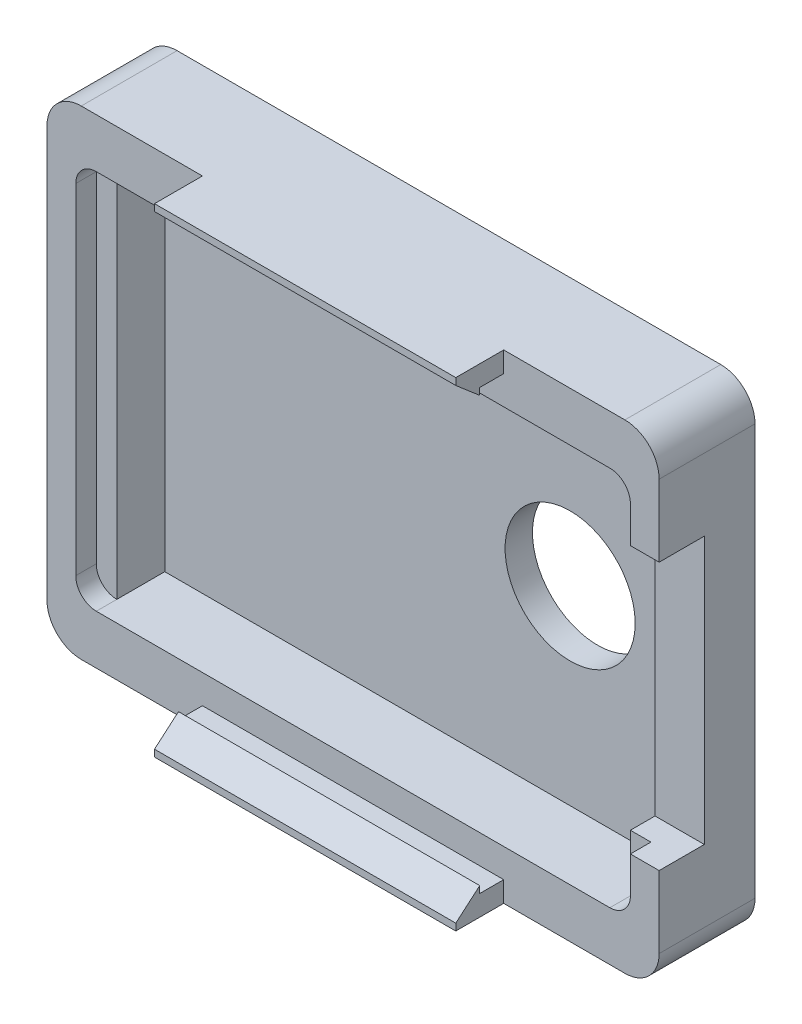
SolidWorks part; units mm, degrees
ref_plane "Alzado" through (0, 0, 0) normal (0, 0, 1) x (1, 0, 0)
ref_plane "Planta" through (0, 0, 0) normal (0, 1, 0) x (1, 0, 0)
ref_plane "Vista lateral" through (0, 0, 0) normal (1, 0, 0) x (0, 0, -1)
sketch "Croquis1" plane through (0, 0, 0) normal (0, 0, 1) x (1, 0, 0)
  line L1 (-22.35, -17.5) -> (22.35, -17.5)
  line L2 (-22.35, -17.5) -> (-22.35, 17.5)
  line L3 (-22.35, 17.5) -> (22.35, 17.5)
  line L4 (22.35, -17.5) -> (22.35, 17.5)
  line L5 (-22.35, -17.5) -> (22.35, 17.5) construction
  line L6 (-22.35, 17.5) -> (22.35, -17.5) construction
  line L11 (-11.35, 14) -> (-6.35, 14)
  line L12 (-11.35, 14) -> (-11.35, 9)
  line L13 (-11.35, 9) -> (-6.35, 9)
  line L14 (-6.35, 14) -> (-6.35, 9)
  circle A0 centre (10.85, 0) radius 4.75
  point P0 (0, 0)
  dimension "D3" = 9.5
  dimension "D1" = 35
  dimension "D2" = 44.7
  dimension "D4" = 11.5
  dimension "D5" = 11
  dimension "D6" = 5
  dimension "D7" = 5
  dimension "D8" = 3.5
extrude "Saliente-Extruir1" add sketch "Croquis1" along normal blind 2 contours L11 L14 L1 L4 L3 L2 L12 A0
sketch "Croquis2" plane through (0, 0, 2) normal (0, 0, 1) x (1, 0, 0)
  line L0 (-22.35, -17.5) -> (22.35, -17.5) construction
  line L1 (22.35, 17.5) -> (-22.35, 17.5) construction
  line L2 (22.35, -17.5) -> (22.35, 17.5) construction
  line L3 (-22.35, 17.5) -> (-22.35, -17.5) construction
  line L4 (-22.35, -17.5) -> (22.35, -17.5)
  line L5 (22.35, 17.5) -> (-22.35, 17.5)
  line L6 (22.35, -17.5) -> (22.35, 17.5)
  line L7 (-22.35, 17.5) -> (-22.35, -17.5)
  line L9 (-20.25, -13.9) -> (20.25, -13.9)
  line L10 (-20.25, -13.9) -> (-20.25, 13.9)
  line L11 (-20.25, 13.9) -> (20.25, 13.9)
  line L12 (20.25, -13.9) -> (20.25, 13.9)
  line L13 (-20.25, -13.9) -> (20.25, 13.9) construction
  line L14 (-20.25, 13.9) -> (20.25, -13.9) construction
  point P4 (0, 0)
  dimension "D1" = 40.5
  dimension "D2" = 27.8
extrude "Saliente-Extruir2" add sketch "Croquis2" along normal blind 5
fillet "Redondeo1" radius 1.5 4 edges at (20.25, -13.9, 4.5) (20.25, 13.9, 4.5) (-20.25, -13.9, 4.5) (-20.25, 13.9, 4.5)
fillet "Redondeo2" radius 2.5 4 edges at (22.35, -17.5, 3.5) (22.35, 17.5, 3.5) (-22.35, -17.5, 3.5) (-22.35, 17.5, 3.5)
sketch "Croquis3" [suppressed] plane through (0, -17.5, 0) normal (0, -1, 0) x (1, 0, 0)
  line L1 (-10.6695, 15.4652) -> (9.8413, 15.4652)
  line L2 (-10.6695, 15.4652) -> (-10.6695, 7.9232)
  line L3 (-10.6695, 7.9232) -> (9.8413, 7.9232)
  line L4 (9.8413, 15.4652) -> (9.8413, 7.9232)
  line L5 (-10.6695, 15.4652) -> (9.8413, 7.9232) construction
  line L6 (-10.6695, 7.9232) -> (9.8413, 15.4652) construction
  point P0 (-0.4141, 11.6942)
sketch "Croquis4" plane through (0, 0, 2) normal (0, 0, 1) x (1, 0, 0)
  line L0 (-20.25, 12.4) -> (-20.25, -12.4) construction
  line L1 (20.25, -12.4) -> (20.25, 12.4) construction
  line L2 (-20.25, 12.4) -> (-20.25, -12.4)
  line L3 (20.25, -12.4) -> (20.25, 12.4)
  line L4 (18.75, -13.9) -> (18.75, 13.9)
  line L5 (-18.75, -13.9) -> (-18.75, 13.9)
  arc A0 (-18.75, 13.9) -> (-20.25, 12.4) centre (-18.75, 12.4) ccw construction
  arc A1 (-20.25, -12.4) -> (-18.75, -13.9) centre (-18.75, -12.4) ccw construction
  arc A2 (20.25, 12.4) -> (18.75, 13.9) centre (18.75, 12.4) ccw construction
  arc A3 (18.75, -13.9) -> (20.25, -12.4) centre (18.75, -12.4) ccw construction
  arc A4 (-18.75, 13.9) -> (-20.25, 12.4) centre (-18.75, 12.4) ccw
  arc A5 (-20.25, -12.4) -> (-18.75, -13.9) centre (-18.75, -12.4) ccw
  arc A6 (20.25, 12.4) -> (18.75, 13.9) centre (18.75, 12.4) ccw
  arc A7 (18.75, -13.9) -> (20.25, -12.4) centre (18.75, -12.4) ccw
extrude "Saliente-Extruir3" add sketch "Croquis4" along normal blind 3.5
sketch "Croquis5" plane through (22.35, 0, 0) normal (1, 0, 0) x (0, 0, -1)
  line L0 (-7, -15) -> (-7, 15) construction
  line L1 (-7, -9.75) -> (-3.7, -9.75)
  line L2 (-7, -9.75) -> (-7, 9.75)
  line L3 (-7, 9.75) -> (-3.7, 9.75)
  line L4 (-3.7, -9.75) -> (-3.7, 9.75)
  point P6 (-3.7, 0)
  dimension "D1" = 19.5
  dimension "D2" = 3.3
extrude "Cortar-Extruir1" cut sketch "Croquis5" against normal blind 5.5
sketch "Croquis6" plane through (0, 0, 7) normal (0, 0, 1) x (1, 0, 0)
  line L0 (-19.85, -17.5) -> (19.85, -17.5) construction
  line L1 (11, -17.5) -> (-11, -17.5)
  line L2 (11, -17.5) -> (11, -15.5)
  line L3 (11, -15.5) -> (-11, -15.5)
  line L4 (-11, -17.5) -> (-11, -15.5)
  line L5 (19.85, 17.5) -> (-19.85, 17.5) construction
  line L6 (11, 17.5) -> (-11, 17.5)
  line L7 (11, 17.5) -> (11, 15.5)
  line L8 (11, 15.5) -> (-11, 15.5)
  line L9 (-11, 17.5) -> (-11, 15.5)
  point P12 (0, -15.5)
  point P14 (0, 17.5)
  point P16 (0, 15.5)
  dimension "D1" = 22
  dimension "D2" = 22
  dimension "D3" = 2
  dimension "D4" = 2
extrude "Saliente-Extruir4" add sketch "Croquis6" along normal blind 3.5
sketch "Croquis7" plane through (11, 0, 0) normal (1, 0, 0) x (0, 0, -1)
  line L0 (-10.5, -17) -> (-8.75, -15.5)
  line L1 (-10.5, -17.5) -> (-10.5, -15.5) construction
  line L2 (-8.75, -15.5) -> (-8.75, -16)
  line L3 (-10.5, 17) -> (-8.75, 15.5)
  line L4 (-10.5, 15.5) -> (-10.5, 17.5) construction
  line L5 (-8.75, -16) -> (-7, -16)
  line L6 (-8.75, 15.5) -> (-8.75, 16)
  line L7 (-8.75, -15.5) -> (-7, -15.5)
  line L8 (-8.75, 16) -> (-7, 16)
  line L9 (-10.5, 15.5) -> (-7, 15.5) construction
  line L10 (-8.75, 15.5) -> (-7, 15.5)
  line L11 (-10.5, -15.5) -> (-7, -15.5) construction
  line L12 (-10.5, -17.5) -> (-7, -17.5) construction
  line L13 (-10.5, 17.5) -> (-7, 17.5) construction
  line L14 (-10.5, -17.5) -> (-7, -17.5)
  line L15 (-10.5, 17.5) -> (-7, 17.5)
  line L16 (-10.5, 17) -> (-10.5, 17.5)
  line L17 (-10.5, -17.5) -> (-10.5, -17)
  line L18 (-7, 15.5) -> (-7, 17.5) construction
  line L19 (-7, -17.5) -> (-7, -15.5) construction
  line L20 (-7, 15.5) -> (-7, 17.5)
  line L21 (-7, -17.5) -> (-7, -15.5)
  line L22 (-10.5, 15.5) -> (-7, 15.5)
  line L23 (-10.5, 15.5) -> (-10.5, 17.5)
  line L24 (-10.5, -17.5) -> (-10.5, -15.5)
  line L25 (-10.5, -15.5) -> (-7, -15.5)
  line M13 (-7, 15.5) -> (-7, 17.5)
  line M15 (-10.5, 17.5) -> (-10.5, 15.5)
  line M16 (-10.5, 15.5) -> (-7, 15.5)
  dimension "D1" = 1.5
  dimension "D2" = 1.5
  dimension "D3" = 1.75
  dimension "D4" = 0.5
  dimension "D5" = 0.5
extrude "Cortar-Extruir2" cut sketch "Croquis7" against normal through all contours L25 L24 L0 | L3 M15 M16 | L8 L6 M16 M13 | L5 L21 L7 L2
